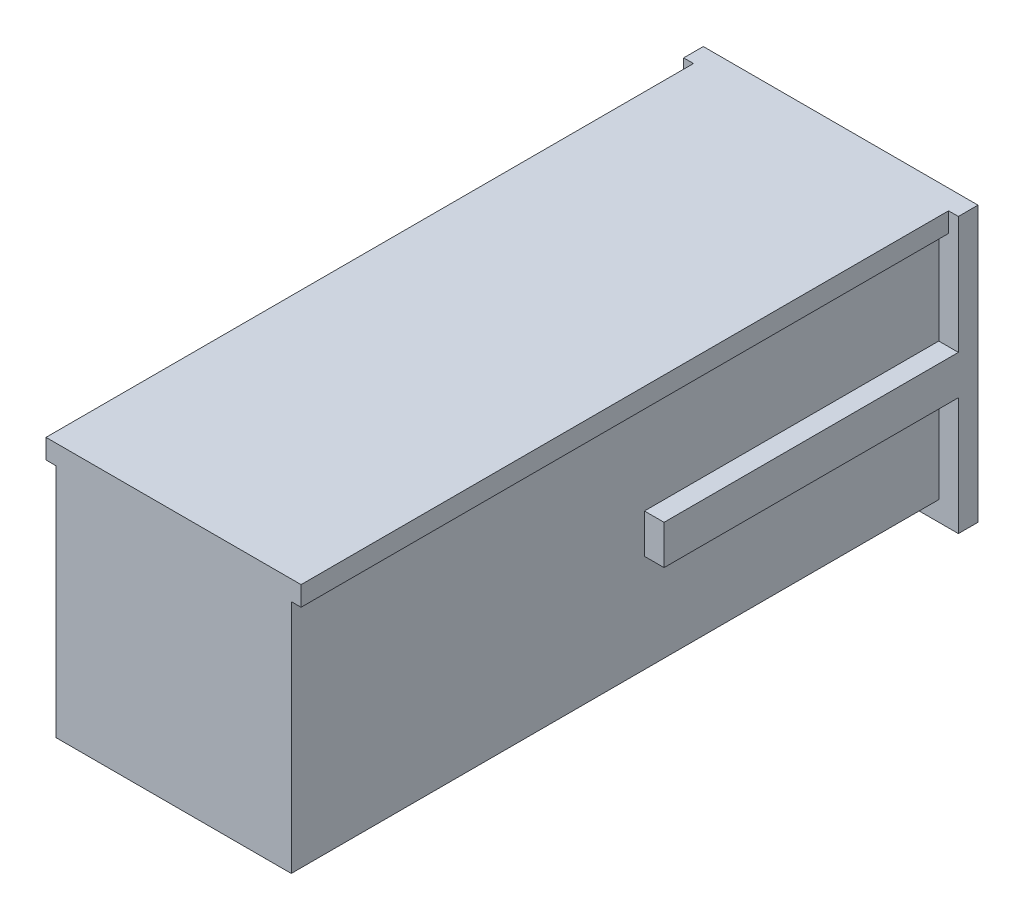
SolidWorks part; units mm, degrees
ref_plane "前视基准面" through (0, 0, 0) normal (0, 0, 1) x (1, 0, 0)
ref_plane "上视基准面" through (0, 0, 0) normal (0, 1, 0) x (1, 0, 0)
ref_plane "右视基准面" through (0, 0, 0) normal (1, 0, 0) x (0, 0, -1)
other "Configuration Table"
sketch "草图1" plane through (0, 0, 0) normal (0, 0, 1) x (1, 0, 0)
  line L1 (-300, -300) -> (300, -300)
  line L2 (-300, -300) -> (-300, 300)
  line L3 (-300, 300) -> (300, 300)
  line L4 (300, -300) -> (300, 300)
  line L5 (-300, -300) -> (300, 300) construction
  line L6 (-300, 300) -> (300, -300) construction
  point P0 (0, 0)
extrude "凸台-拉伸1" add sketch "草图1" along normal blind 1700
sketch "草图2" plane through (0, 0, 0) normal (0, 0, 1) x (1, 0, 0)
  line L1 (-325, 300) -> (325, 300)
  line L2 (-325, 300) -> (-325, 350)
  line L3 (-325, 350) -> (325, 350)
  line L4 (325, 300) -> (325, 350)
  line L5 (-325, 300) -> (325, 350) construction
  line L6 (-325, 350) -> (325, 300) construction
  point P0 (0, 325)
extrude "凸台-拉伸2" add sketch "草图2" along normal blind 1700
sketch "草图3" plane through (0, 0, 0) normal (0, 0, 1) x (1, 0, 0)
  line L1 (300, -50) -> (350, -50)
  line L2 (300, -50) -> (300, 50)
  line L3 (300, 50) -> (350, 50)
  line L4 (350, -50) -> (350, 50)
  line L5 (300, -50) -> (350, 50) construction
  line L6 (300, 50) -> (350, -50) construction
  point P0 (325, 0)
extrude "凸台-拉伸3" add sketch "草图3" along normal blind 800
sketch "草图4" plane through (0, 0, 0) normal (0, 0, 1) x (1, 0, 0)
  line L1 (-350, -350) -> (350, -350)
  line L2 (-350, -350) -> (-350, 350)
  line L3 (-350, 350) -> (350, 350)
  line L4 (350, -350) -> (350, 350)
  line L5 (-350, -350) -> (350, 350) construction
  line L6 (-350, 350) -> (350, -350) construction
  point P0 (0, 0)
extrude "凸台-拉伸4" add sketch "草图4" along normal blind 50
